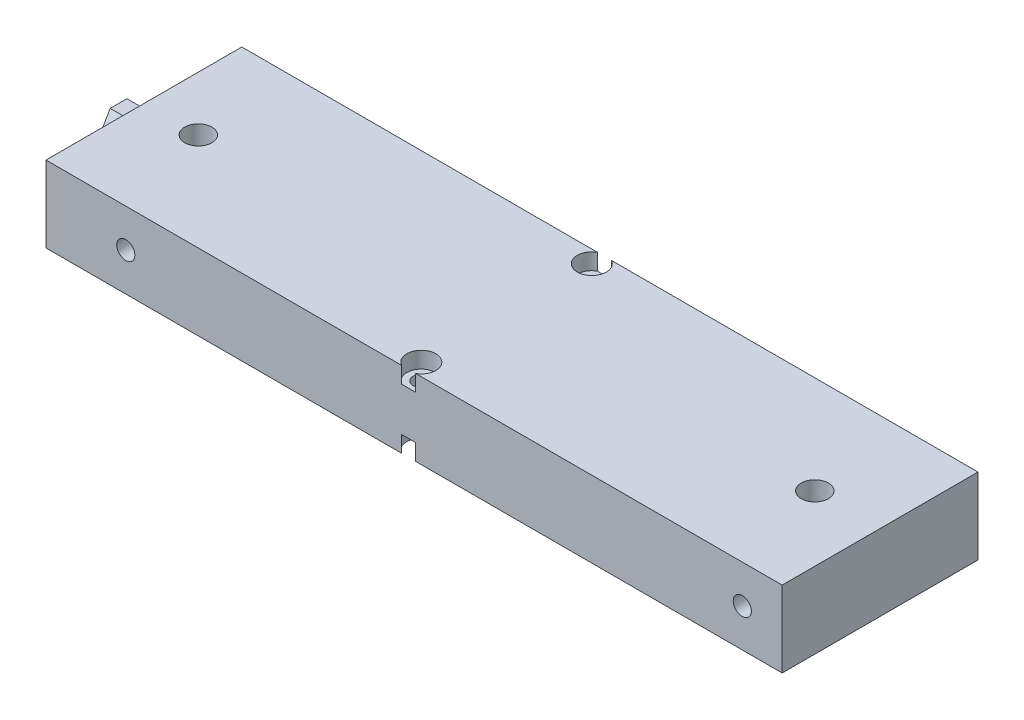
SolidWorks part; units mm, degrees
ref_plane "前视基准面" through (0, 0, 0) normal (0, 0, 1) x (1, 0, 0)
ref_plane "上视基准面" through (0, 0, 0) normal (0, 1, 0) x (1, 0, 0)
ref_plane "右视基准面" through (0, 0, 0) normal (1, 0, 0) x (0, 0, -1)
sketch "草图1" plane through (0, 0, 0) normal (0, 1, 0) x (1, 0, 0)
  line L1 (0, 0) -> (203, 0)
  line L2 (0, 0) -> (0, 54)
  line L3 (0, 54) -> (203, 54)
  line L4 (203, 0) -> (203, 54)
  dimension "D1" = 203
  dimension "D2" = 54
extrude "凸台-拉伸1" add sketch "草图1" along normal blind 21
sketch "草图2" plane through (0, 0, 0) normal (-1, 0, 0) x (0, 0, 1)
  line L0 (-27, 21) -> (-27, 0) construction
  line L1 (-54, 21) -> (0, 21) construction
  line L2 (-54, 0) -> (0, 0) construction
  circle A0 centre (-15, 10.5) radius 4
  circle A1 centre (-39, 10.5) radius 4
  point P6 (-27, 10.5)
  dimension "D1" = 8
  dimension "D2" = 24
extrude "切除-拉伸1" cut sketch "草图2" against normal blind 150
sketch "草图3" plane through (0, 21, 0) normal (0, 1, 0) x (1, 0, 0)
  line L0 (0, 27) -> (203, 27) construction
  line L1 (0, 54) -> (0, 0) construction
  line L2 (203, 0) -> (203, 54) construction
  circle A0 centre (100, 3.5) radius 2.25
  circle A1 centre (100, 50.5) radius 2.25
  circle A2 centre (15, 27) radius 2.25
  circle A3 centre (185, 27) radius 2.25
  dimension "D1" = 47
  dimension "D2" = 4.5
  dimension "D3" = 100
  dimension "D4" = 4.5
  dimension "D5" = 4.5
  dimension "D7" = 170
  dimension "D6" = 15
extrude "切除-拉伸2" cut sketch "草图3" against normal through all
sketch "草图4" plane through (0, 21, 0) normal (0, 1, 0) x (1, 0, 0)
  circle A1 centre (100, 50.5) radius 4
  circle A2 centre (100, 3.5) radius 4
  circle A4 centre (100, 50.5) radius 2.25 construction
  dimension "D3" = 8
  dimension "D4" = 8
extrude "切除-拉伸3" cut sketch "草图4" against normal blind 4.5
sketch "草图5" plane through (0, 21, 0) normal (0, 1, 0) x (1, 0, 0)
  circle A0 centre (185, 27) radius 3.75
  circle A1 centre (15, 27) radius 3.75
  dimension "D1" = 7.5
  dimension "D2" = 7.5
extrude "切除-拉伸4" cut sketch "草图5" against normal blind 7.2
ref_plane "基准面1" through (0, 10.5, 0) normal (0, -1, 0) x (-1, 0, 0)
mirror "镜向1" about plane through (0, 10.5, 0) normal (0, -1, 0) of "切除-拉伸3", "切除-拉伸4"
sketch "草图6" plane through (0, 0, 0) normal (0, 0, 1) x (1, 0, 0)
  line L0 (0, 10.5) -> (203, 10.5) construction
  line L1 (0, 21) -> (0, 0) construction
  line L2 (203, 21) -> (203, 0) construction
  circle A0 centre (22, 10.5) radius 2.5
  circle A1 centre (192, 10.5) radius 2.5
  dimension "D1" = 5
  dimension "D2" = 5
  dimension "D3" = 22
  dimension "D4" = 11
extrude "切除-拉伸5" cut sketch "草图6" against normal blind 5
cosmetic thread "装饰螺纹线1" parameters "D2"=6
cosmetic thread "装饰螺纹线2" parameters "D2"=6
sketch "草图7" plane through (0, 0, 0) normal (-1, 0, 0) x (0, 0, 1)
  line L0 (0, 10.5) -> (-54, 10.5) construction
  line L1 (0, 21) -> (0, 0) construction
  line L2 (-54, 21) -> (-54, 0) construction
  line L3 (-27, 10.5) -> (-27, 13.5) construction
  line L5 (-24.6906, 17.5) -> (-29.3094, 17.5)
  line L6 (-29.3094, 17.5) -> (-31.6188, 13.5)
  line L7 (-31.6188, 13.5) -> (-29.3094, 9.5)
  line L8 (-29.3094, 9.5) -> (-24.6906, 9.5)
  line L9 (-24.6906, 9.5) -> (-22.3812, 13.5)
  line L10 (-22.3812, 13.5) -> (-24.6906, 17.5)
  circle A0 centre (-27, 13.5) radius 4 construction
  circle A1 centre (-27, 13.5) radius 4.6188 construction
  point P9 (-27, 17.5)
  point P17 (-27, 17.5)
  dimension "D2" = 8
  dimension "D1" = 3
extrude "凸台-拉伸2" add sketch "草图7" along normal blind 7
